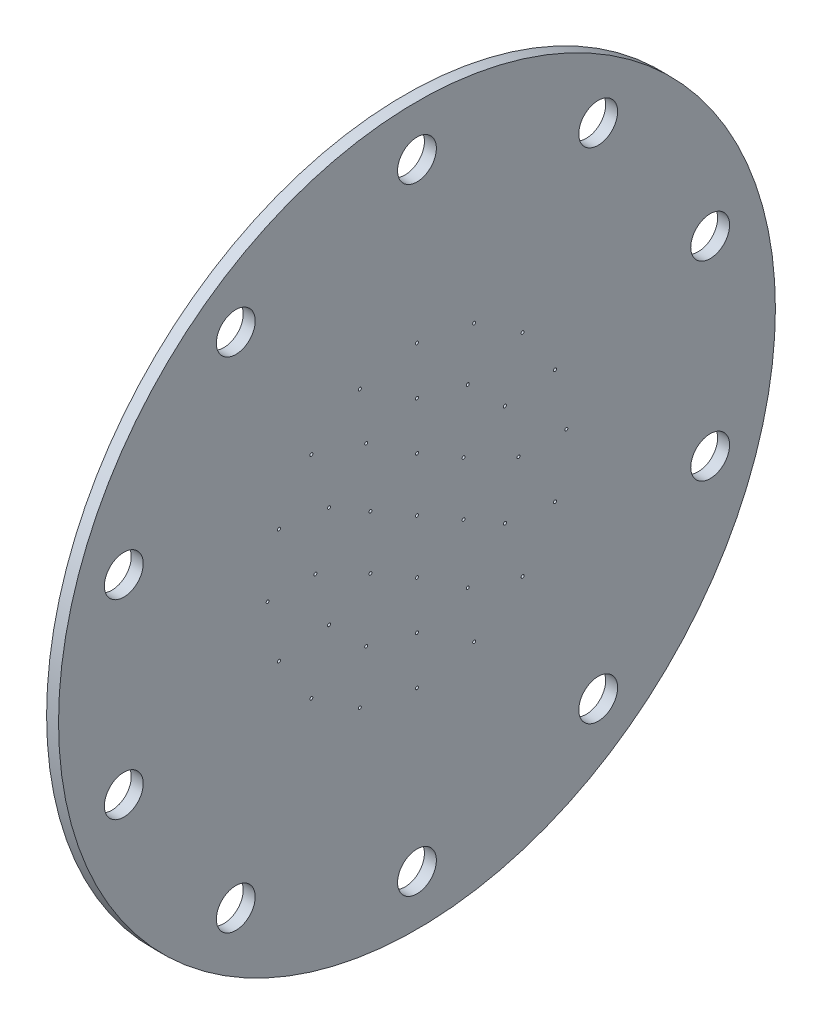
SolidWorks part; units mm, degrees
material "AISI 316 Stainless Steel Sheet (SS)"
ref_plane "Front Plane" through (0, 0, 0) normal (0, 0, 1) x (1, 0, 0)
ref_plane "Top Plane" through (0, 0, 0) normal (0, 1, 0) x (1, 0, 0)
ref_plane "Right Plane" through (0, 0, 0) normal (1, 0, 0) x (0, 0, -1)
sketch "Sketch2" plane through (0, 0, 0) normal (0, 0, 1) x (1, 0, 0)
  line L0 (2, 0) -> (2, 31)
  line L1 (0, 0) -> (2, 0)
  line L2 (0, 0) -> (0, 60)
  line L3 (0, 60) -> (2, 60)
  line L4 (2, 31) -> (2, 60)
  dimension "thickness" = 2
  dimension "catbed_radius" = 31
  dimension "step" = 29
revolve "Revolve1" add sketch "Sketch2" angle 360 about L1
sketch "Sketch3" plane through (0, 0, 0) normal (-1, 0, 0) x (0, 0, 1)
  line L0 (0, 0) -> (0, 9) construction
  line L1 (0, 9) -> (0, 17) construction
  line L2 (0, 17) -> (0, 25) construction
  circle A0 centre (0, 0) radius 0.25
  circle A1 centre (0, 9) radius 0.25
  circle A2 centre (0, 17) radius 0.25
  circle A3 centre (0, 25) radius 0.25
  circle A4 centre (7.7942, 4.5) radius 0.25
  circle A5 centre (7.7942, -4.5) radius 0.25
  circle A6 centre (0, -9) radius 0.25
  circle A7 centre (-7.7942, -4.5) radius 0.25
  circle A8 centre (-7.7942, 4.5) radius 0.25
  circle A9 centre (8.5, 14.7224) radius 0.25
  circle A10 centre (14.7224, 8.5) radius 0.25
  circle A11 centre (17, 0) radius 0.25
  circle A12 centre (14.7224, -8.5) radius 0.25
  circle A13 centre (8.5, -14.7224) radius 0.25
  circle A14 centre (0, -17) radius 0.25
  circle A15 centre (-8.5, -14.7224) radius 0.25
  circle A16 centre (-14.7224, -8.5) radius 0.25
  circle A17 centre (-17, 0) radius 0.25
  circle A18 centre (-14.7224, 8.5) radius 0.25
  circle A19 centre (-8.5, 14.7224) radius 0.25
  circle A20 centre (9.5671, 23.097) radius 0.25
  circle A21 centre (17.6777, 17.6777) radius 0.25
  circle A22 centre (23.097, 9.5671) radius 0.25
  circle A23 centre (25, 0) radius 0.25
  circle A24 centre (23.097, -9.5671) radius 0.25
  circle A25 centre (17.6777, -17.6777) radius 0.25
  circle A26 centre (9.5671, -23.097) radius 0.25
  circle A27 centre (0, -25) radius 0.25
  circle A28 centre (-9.5671, -23.097) radius 0.25
  circle A29 centre (-17.6777, -17.6777) radius 0.25
  circle A30 centre (-23.097, -9.5671) radius 0.25
  circle A31 centre (-25, 0) radius 0.25
  circle A32 centre (-23.097, 9.5671) radius 0.25
  circle A33 centre (-17.6777, 17.6777) radius 0.25
  circle A34 centre (-9.5671, 23.097) radius 0.25
  point P21 (0, 0)
  point P45 (0, 0)
  point P75 (0, 0)
  dimension "D1" = 9
  dimension "centre_hole" = 0.5
  dimension "D5" = 8
  dimension "D6" = 8
  dimension "D2" = 6
  dimension "D3" = 12
  dimension "D4" = 16
extrude "Cut-Extrude1" cut sketch "Sketch3" against normal through all
sketch "Sketch4" plane through (0, 0, 0) normal (-1, 0, 0) x (0, 0, 1)
  line L0 (0, 0) -> (0, 51.6) construction
  circle A0 centre (0, 0) radius 60 construction
  circle A2 centre (0, 51.6) radius 3.25
  circle A3 centre (30.3297, 41.7453) radius 3.25
  circle A4 centre (49.0745, 15.9453) radius 3.25
  circle A5 centre (49.0745, -15.9453) radius 3.25
  circle A6 centre (30.3297, -41.7453) radius 3.25
  circle A7 centre (0, -51.6) radius 3.25
  circle A8 centre (-30.3297, -41.7453) radius 3.25
  circle A9 centre (-49.0745, -15.9453) radius 3.25
  circle A10 centre (-49.0745, 15.9453) radius 3.25
  circle A11 centre (-30.3297, 41.7453) radius 3.25
  point P27 (0, 0)
  dimension "D1" = 51.6
  dimension "D2" = 6.5
  dimension "D3" = 10
extrude "Cut-Extrude2" cut sketch "Sketch4" against normal blind 10
